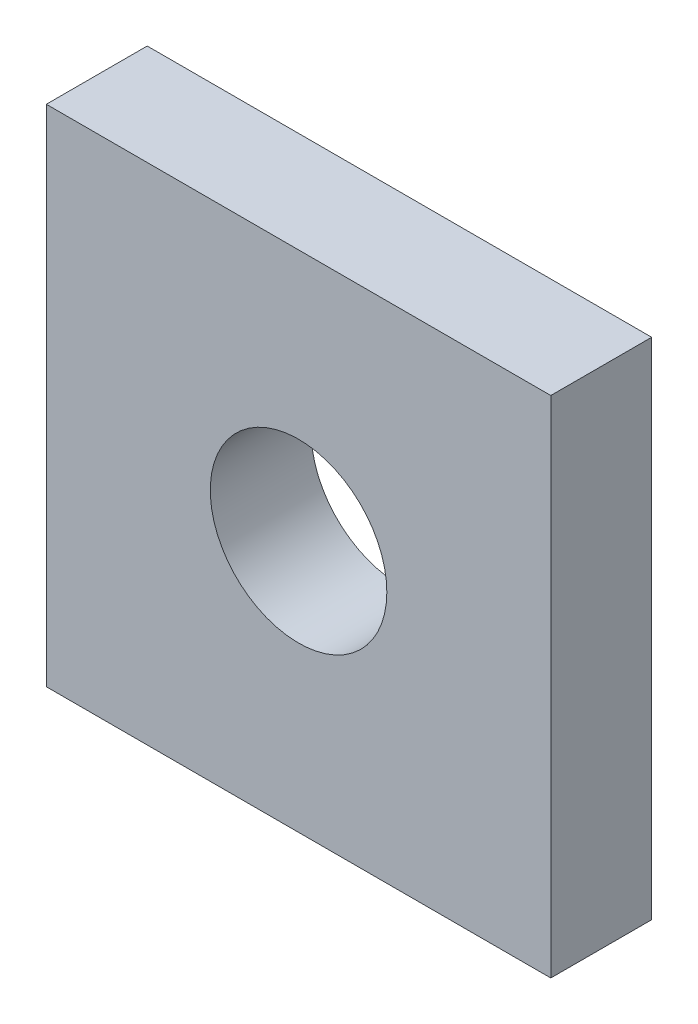
SolidWorks part; units mm, degrees
ref_plane "前视基准面" through (0, 0, 0) normal (0, 0, 1) x (1, 0, 0)
ref_plane "上视基准面" through (0, 0, 0) normal (0, 1, 0) x (1, 0, 0)
ref_plane "右视基准面" through (0, 0, 0) normal (1, 0, 0) x (0, 0, -1)
sketch "草图1" plane through (0, 0, 0) normal (0, 0, 1) x (1, 0, 0)
  line L1 (-25, -25) -> (25, -25)
  line L2 (-25, -25) -> (-25, 25)
  line L3 (-25, 25) -> (25, 25)
  line L4 (25, -25) -> (25, 25)
  line L5 (-25, -25) -> (25, 25) construction
  line L6 (-25, 25) -> (25, -25) construction
  circle A0 centre (0, 0) radius 8.75
  point P0 (0, 0)
  dimension "D3" = 17.5
  dimension "D1" = 50
  dimension "D2" = 50
extrude "凸台-拉伸1" add sketch "草图1" along normal blind 10
